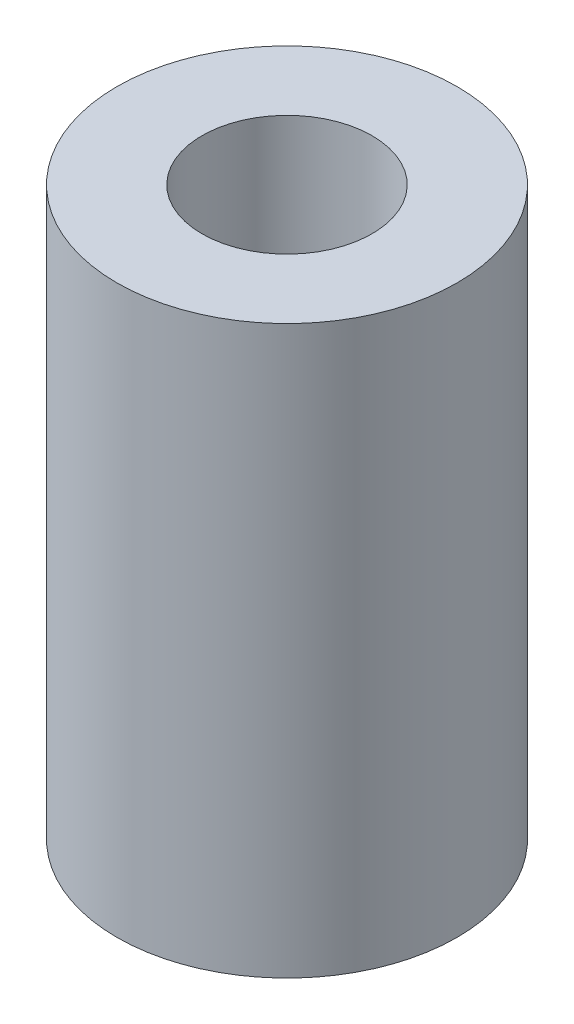
SolidWorks part; units mm, degrees
ref_plane "Plano frontal" through (0, 0, 0) normal (0, 0, 1) x (1, 0, 0)
ref_plane "Plano superior" through (0, 0, 0) normal (0, 1, 0) x (1, 0, 0)
ref_plane "Plano direito" through (0, 0, 0) normal (1, 0, 0) x (0, 0, -1)
sketch "Sketch1" plane through (0, 0, 0) normal (0, 1, 0) x (1, 0, 0)
  circle A1 centre (0, 0) radius 6
extrude "Boss-Extrude3" add sketch "Sketch1" along normal blind 20
sketch "Sketch5" plane through (0, 20, 0) normal (0, 1, 0) x (1, 0, 0)
  circle A0 centre (0, 0) radius 3
extrude "Cut-Extrude2" cut sketch "Sketch5" against normal blind 9
sketch "Sketch6" plane through (0, 0, 0) normal (0, -1, 0) x (1, 0, 0)
  circle A0 centre (0, 0) radius 1
extrude "Cut-Extrude3" cut sketch "Sketch6" against normal blind 9
